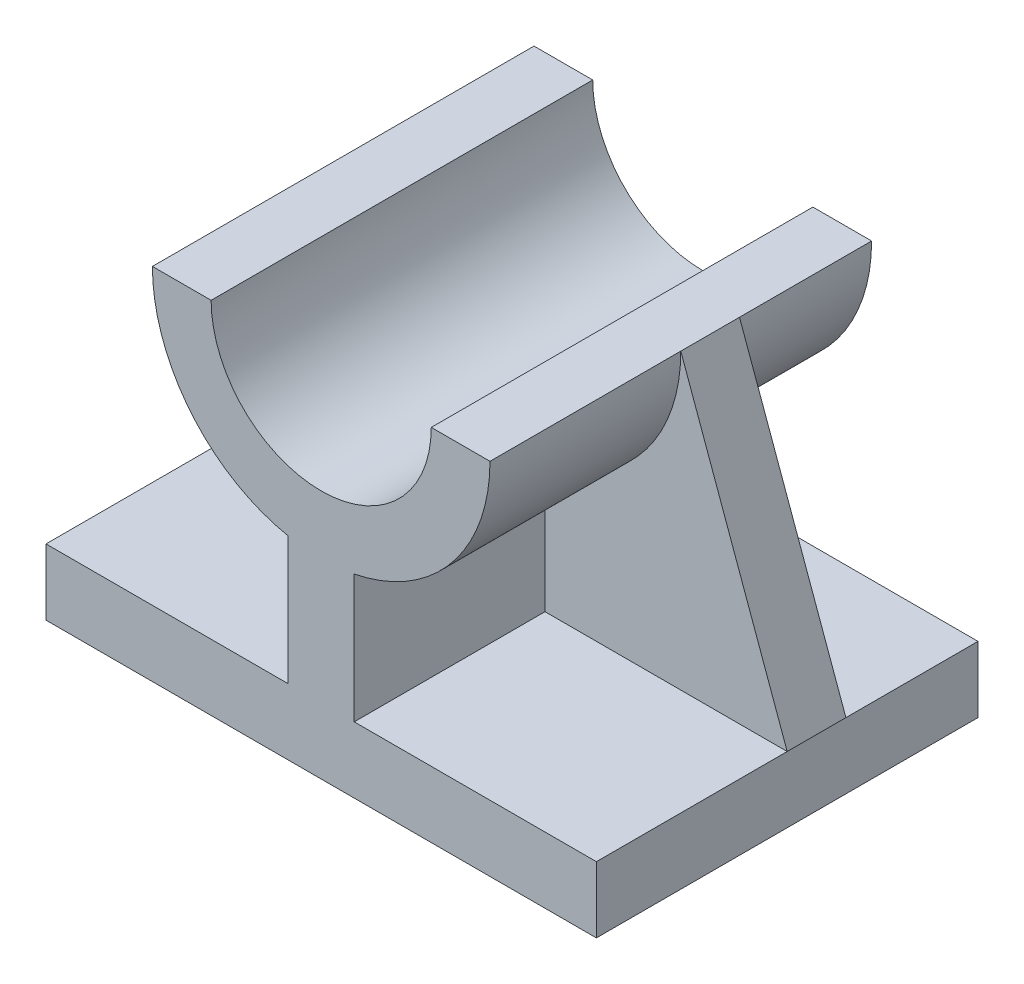
SolidWorks part; units mm, degrees
ref_plane "Front Plane" through (0, 0, 0) normal (0, 0, 1) x (1, 0, 0)
ref_plane "Top Plane" through (0, 0, 0) normal (0, 1, 0) x (1, 0, 0)
ref_plane "Right Plane" through (0, 0, 0) normal (1, 0, 0) x (0, 0, -1)
sketch "Sketch1" plane through (0, 0, 0) normal (0, 1, 0) x (1, 0, 0)
  line L1 (0, 0) -> (75, 0)
  line L2 (0, 0) -> (0, 52)
  line L3 (0, 52) -> (75, 52)
  line L4 (75, 0) -> (75, 52)
  dimension "D1" = 75
  dimension "D2" = 52
extrude "Boss-Extrude1" add sketch "Sketch1" along normal blind 9
sketch "Sketch2" plane through (0, 0, 0) normal (0, 0, 1) x (1, 0, 0)
  line L0 (33, 9) -> (33, 26.4445)
  line L1 (0, 9) -> (75, 9) construction
  line L2 (42, 9) -> (42, 26.4445)
  line L3 (0, 9) -> (0, 0) construction
  line L4 (37.5, 92.686) -> (37.5, -1.8942) construction
  line L5 (-6.3416, 49) -> (75.8871, 49) construction
  line L6 (14.5, 49) -> (22.5, 49)
  line L7 (52.5, 49) -> (60.5, 49)
  line L12 (0, 0) -> (75, 0)
  line L13 (75, 0) -> (75, 9)
  line L14 (75, 9) -> (0, 9)
  line L15 (0, 9) -> (0, 0)
  line L18 (42, 9) -> (33, 9)
  arc A0 (42, 26.4445) -> (60.5, 49) centre (37.5, 49) ccw
  arc A1 (22.5, 49) -> (52.5, 49) centre (37.5, 49) ccw
  arc A2 (14.5, 49) -> (33, 26.4445) centre (37.5, 49) ccw
  dimension "D5" = 30
  dimension "D6" = 46
  dimension "D1" = 9
  dimension "D2" = 33
  dimension "D3" = 4.5
  dimension "D4" = 40
  dimension "D7" = 0
extrude "Boss-Extrude2" add sketch "Sketch2" against normal blind 52
ref_plane "Plane1" through (0, 0, -30) normal (0, 0, 1) x (1, 0, 0)
sketch "Sketch5" plane through (0, 0, -30) normal (0, 0, 1) x (1, 0, 0)
  line L0 (60.5, 49) -> (75, 9)
  arc A0 (42, 26.4445) -> (60.5, 49) centre (37.5, 49) ccw construction
rib "Rib2" sketch "Sketch5" sketch "Sketch5" thickness 8 extrusion direction parallel to sketch draft on no parameters "D1"=8
ref_plane "Plane4" through (37.5, 0, 0) normal (1, 0, 0) x (0, 0, -1)
mirror "Mirror2" about plane through (37.5, 0, 0) normal (1, 0, 0) of "Rib2"
